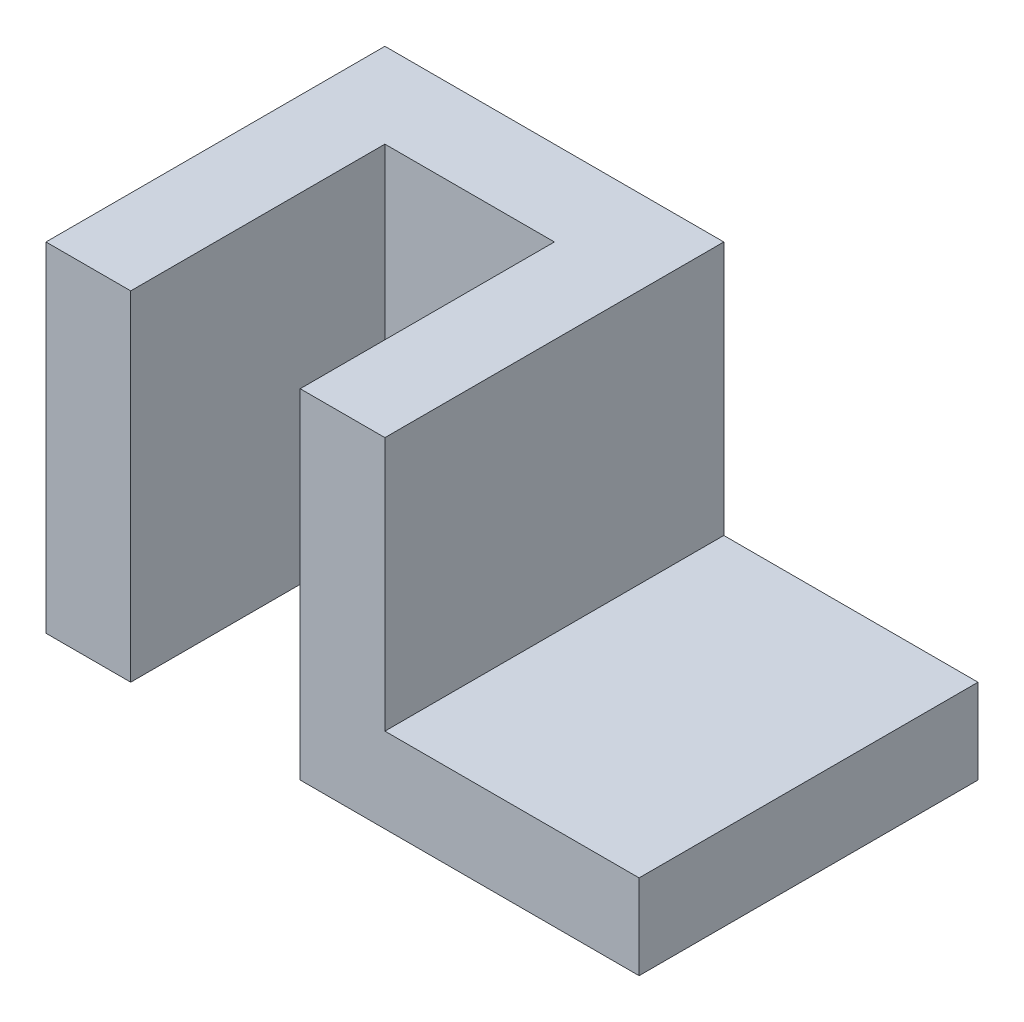
SolidWorks part; units mm, degrees
ref_plane "Front Plane" through (0, 0, 0) normal (0, 0, 1) x (1, 0, 0)
ref_plane "Top Plane" through (0, 0, 0) normal (0, 1, 0) x (1, 0, 0)
ref_plane "Right Plane" through (0, 0, 0) normal (1, 0, 0) x (0, 0, -1)
sketch "Sketch1" plane through (0, 0, 0) normal (0, 1, 0) x (1, 0, 0)
  line L0 (0, 0) -> (0, 40)
  line L1 (0, 40) -> (40, 40)
  line L2 (40, 40) -> (40, 0)
  line L3 (40, 0) -> (30, 0)
  line L4 (30, 0) -> (30, 30)
  line L5 (30, 30) -> (10, 30)
  line L6 (10, 30) -> (10, 0)
  line L7 (10, 0) -> (0, 0)
  dimension "D1" = 40
  dimension "D2" = 10
  dimension "D3" = 10
  dimension "D4" = 10
  dimension "D5" = 20
extrude "Boss-Extrude1" add sketch "Sketch1" along normal blind 40
sketch "Sketch2" plane through (40, 0, 0) normal (1, 0, 0) x (0, 0, -1)
  line L0 (40, 40) -> (40, 0) construction
  line L1 (0, 0) -> (40, 0)
  line L2 (0, 0) -> (0, 10)
  line L3 (0, 10) -> (40, 10)
  line L4 (40, 0) -> (40, 10)
  dimension "D1" = 10
  dimension "D2" = 40
extrude "Boss-Extrude2" add sketch "Sketch2" along normal blind 30
